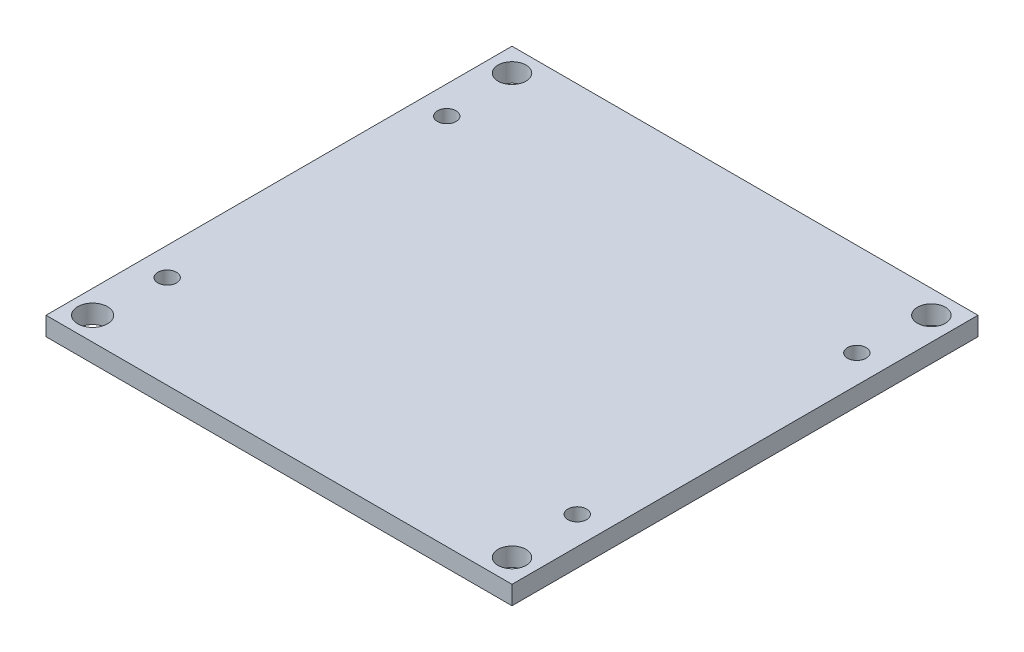
SolidWorks part; units mm, degrees
ref_plane "Front Plane" through (0, 0, 0) normal (0, 0, 1) x (1, 0, 0)
ref_plane "Top Plane" through (0, 0, 0) normal (0, 1, 0) x (1, 0, 0)
ref_plane "Right Plane" through (0, 0, 0) normal (1, 0, 0) x (0, 0, -1)
sketch "Sketch1" plane through (0, 0, 0) normal (0, 1, 0) x (1, 0, 0)
  line L1 (0, 0) -> (50, 0)
  line L2 (0, 0) -> (0, 50)
  line L3 (0, 50) -> (50, 50)
  line L4 (50, 0) -> (50, 50)
  dimension "D1" = 50
  dimension "D2" = 50
extrude "Boss-Extrude1" add sketch "Sketch1" along normal blind 2
hole_wizard "M3 Clearance Hole1" positions "Sketch3" profile "Sketch4" hole size "M3" standard "ANSI Metric" end condition through all
sketch "Sketch3" plane through (0, 2, 0) normal (0, 1, 0) x (1, 0, 0)
  line L0 (0, 0) -> (50, 0) construction
  line L1 (0, 50) -> (0, 0) construction
  point P0 (2.5, 2.5)
  dimension "D1" = 2.5
  dimension "D2" = 2.5
sketch "Sketch4" plane through (2.5, 2, -2.5) normal (1, 0, 0) x (0, 0, 1)
  line L0 (0, 0) -> (0, 2)
  line L1 (0, 2) -> (1.6, 2)
  line L2 (1.6, 2) -> (1.6, 0)
  line L5 (1.6, 0) -> (0, 0)
  line L11 (0, -6.35) -> (0, 107.95) construction
  dimension "Thru Hole Dia." = 3.2
  dimension "Thru Hole Depth" = 2
hole_wizard "M3 Clearance Hole2" positions "Sketch7" profile "Sketch5" hole size "M3" standard "ANSI Metric" end condition through all
sketch "Sketch7" plane through (0, 2, 0) normal (0, 1, 0) x (1, 0, 0)
  line L2 (50, 50) -> (0, 50) construction
  line L3 (0, 50) -> (0, 0) construction
  line L5 (50, 0) -> (50, 50) construction
  line L6 (0, 0) -> (50, 0) construction
  point P0 (47.5, 2.5)
  point P2 (47.5, 47.5)
  point P4 (2.5, 47.5)
  dimension "D1" = 2.5
  dimension "D2" = 2.5
  dimension "D3" = 45
  dimension "D4" = 2.5
  dimension "D5" = 2.5
  dimension "D6" = 2.5
  dimension "D7" = 45
  dimension "D8" = 2.5
sketch "Sketch5" plane through (47.5, 2, -2.5) normal (1, 0, 0) x (0, 0, 1)
  line L0 (0, 0) -> (0, 2)
  line L1 (0, 2) -> (1.5, 2)
  line L2 (1.5, 2) -> (1.5, 0)
  line L5 (1.5, 0) -> (0, 0)
  line L11 (0, -6.35) -> (0, 107.95) construction
  dimension "Thru Hole Dia." = 3
  dimension "Thru Hole Depth" = 2
hole_wizard "M2 Clearance Hole1" positions "Sketch9" profile "Sketch8" hole size "M2" standard "ANSI Metric"
sketch "Sketch9" plane through (0, 2, 0) normal (0, 1, 0) x (1, 0, 0)
  line L0 (50, 0) -> (50, 50) construction
  line L1 (0, 50) -> (0, 0) construction
  line L2 (50, 50) -> (0, 50) construction
  line L3 (0, 0) -> (50, 0) construction
  point P0 (3, 10)
  point P2 (3, 40)
  point P4 (47, 40)
  point P6 (47, 10)
  dimension "D1" = 44
  dimension "D2" = 44
  dimension "D3" = 30
  dimension "D4" = 3
  dimension "D5" = 3
  dimension "D6" = 10
  dimension "D7" = 10
  dimension "D8" = 30
sketch "Sketch8" plane through (3, 2, -10) normal (1, 0, 0) x (0, 0, 1)
  line L0 (0, 0) -> (0, 10.6009)
  line L1 (0, 10.6009) -> (1, 10)
  line L2 (1, 10) -> (1, 0)
  line L5 (1, 0) -> (0, 0)
  line L10 (0, 10.6009) -> (-1, 10) construction
  line L11 (0, -6.35) -> (0, 107.95) construction
  dimension "Hole Dia." = 2
  dimension "Hole Depth" = 10
  dimension "Drill Angle" = 118
